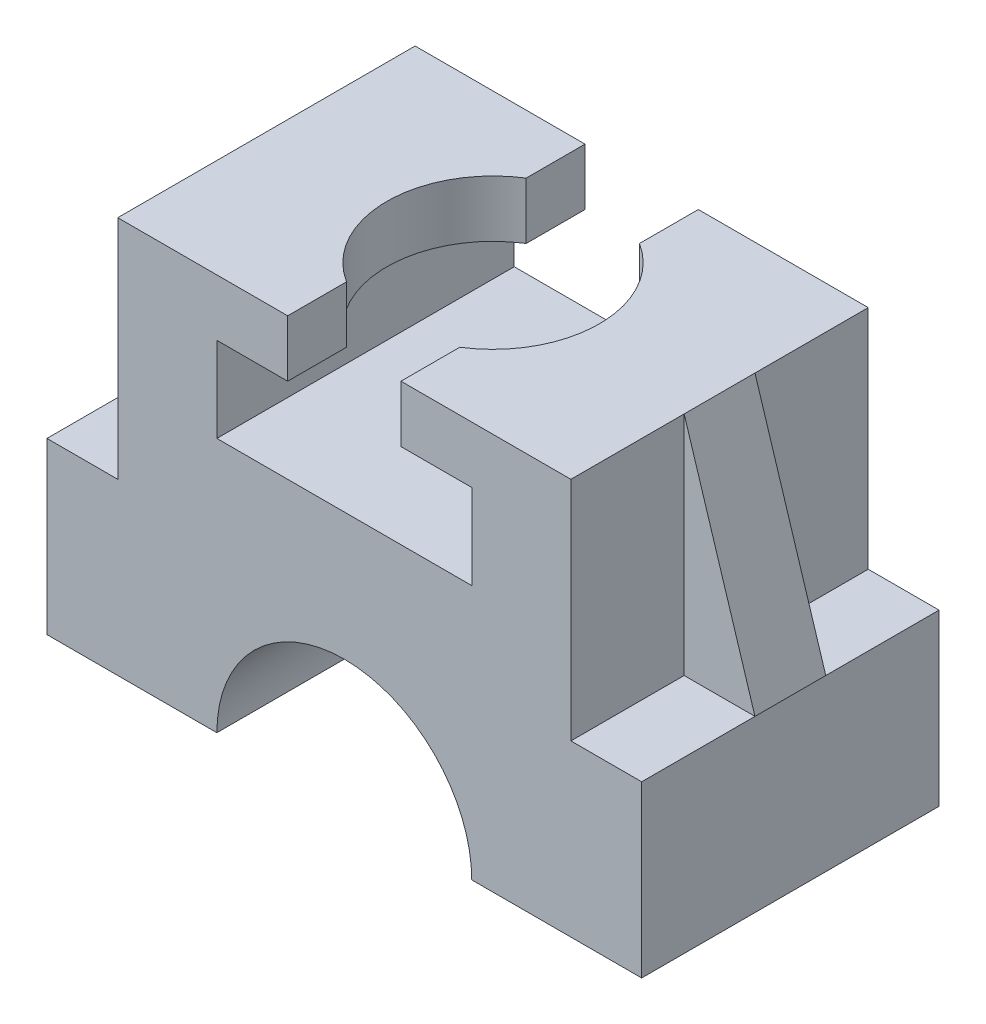
SolidWorks part; units mm, degrees
ref_plane "Front Plane" through (0, 0, 0) normal (0, 0, 1) x (1, 0, 0)
ref_plane "Top Plane" through (0, 0, 0) normal (0, 1, 0) x (1, 0, 0)
ref_plane "Right Plane" through (0, 0, 0) normal (1, 0, 0) x (0, 0, -1)
sketch "Sketch1" plane through (0, 0, 0) normal (0, 0, 1) x (1, 0, 0)
  line L0 (-80, 80) -> (-80, 0)
  line L1 (-80, 80) -> (-20, 80)
  line L2 (-105, 0) -> (-105, -60)
  line L3 (-105, -60) -> (-45, -60)
  line L4 (105, 0) -> (105, -60)
  line L5 (80, 80) -> (80, 0)
  line L6 (-105, 0) -> (-80, 0)
  line L7 (80, 0) -> (105, 0)
  line L8 (-105, 80) -> (-105, -60) construction
  line L9 (105, 80) -> (105, -60) construction
  line L10 (-80, 80) -> (-80, -60) construction
  line L11 (80, 80) -> (80, -60) construction
  line L12 (45, -60) -> (105, -60)
  line L13 (-105, 0) -> (105, 0) construction
  line L14 (20, 80) -> (80, 80)
  line L15 (-105, -60) -> (105, -60) construction
  line L17 (-80, 80) -> (80, 80) construction
  line L18 (-45, 60) -> (-20, 60)
  line L19 (-45, 30) -> (45, 30)
  line L20 (20, 60) -> (45, 60)
  line L22 (45, 30) -> (45, 60)
  line L23 (-80, 60) -> (80, 60) construction
  line L24 (-45, 30) -> (-45, 60)
  line L25 (-20, 60) -> (-20, 80)
  line L26 (20, 60) -> (20, 80)
  line L30 (-80, 30) -> (80, 30) construction
  arc A0 (45, -60) -> (-45, -60) centre (0, -60) ccw
  point P0 (0, 0)
  point P15 (0, 80)
  point P18 (502.4014, 219.5532)
  point P20 (515.5847, -78.9157)
  point P29 (20, 70)
  point P31 (502.4014, 219.5532)
  point P33 (515.5847, -78.9157)
  dimension "D4" = 45
  dimension "D5" = 105
  dimension "D6" = 60
  dimension "D7" = 80
  dimension "D8" = 60
  dimension "D9" = 20
  dimension "D10" = 20
  dimension "D13" = 105
  dimension "D2" = 80
  dimension "D1" = 25
  dimension "D3" = 60
  dimension "D11" = 20
  dimension "D12" = 30
extrude "Boss-Extrude1" add sketch "Sketch1" against normal blind 105
sketch "Sketch2" plane through (0, 80, 0) normal (0, 1, 0) x (1, 0, 0)
  circle A0 centre (0, 52.5) radius 37.5
  dimension "D1" = 75
  dimension "D2" = 52.5
extrude "Cut-Extrude1" cut sketch "Sketch2" against normal blind 20
sketch "Sketch3" plane through (80, 0, 0) normal (1, 0, 0) x (0, 0, -1)
  line L0 (105, 80) -> (0, 80) construction
  line L1 (40, 0) -> (65, 0)
  line L2 (40, 0) -> (40, 80)
  line L3 (40, 80) -> (65, 80)
  line L4 (65, 0) -> (65, 80)
  line L5 (105, 0) -> (105, 80) construction
  line L6 (0, 0) -> (0, 80) construction
  line L7 (105, 0) -> (0, 0) construction
  point P0 (52.3048, 40)
  dimension "D1" = 0
  dimension "D2" = 40
  dimension "D3" = 40
  dimension "D4" = 40
extrude "Boss-Extrude2" add sketch "Sketch3" along normal blind 25
sketch "Sketch5" plane through (-80, 0, 0) normal (-1, 0, 0) x (0, 0, 1)
  line L0 (-105, 80) -> (0, 80) construction
  line L1 (-40, 0) -> (-65, 0)
  line L2 (-40, 0) -> (-40, 80)
  line L3 (-40, 80) -> (-65, 80)
  line L4 (-65, 0) -> (-65, 80)
  line L7 (-105, 0) -> (0, 0) construction
  line L8 (-105, 80) -> (-105, 0) construction
  line L9 (0, 80) -> (0, 0) construction
  point P0 (-52.5, 40)
  dimension "D1" = 0
  dimension "D2" = 40
  dimension "D3" = 40
extrude "Boss-Extrude3" add sketch "Sketch5" along normal blind 25
sketch "Sketch6" plane through (0, 0, -65) normal (0, 0, -1) x (-1, 0, 0)
  line L0 (80, 80) -> (105, 80)
  line L1 (105, 80) -> (105, 0)
  line L2 (105, 0) -> (80, 80)
  line L3 (-105, 0) -> (-105, 80)
  line L4 (-105, 80) -> (-80, 80)
  line L5 (-80, 80) -> (-105, 0)
extrude "Cut-Extrude2" cut sketch "Sketch6" against normal blind 25
